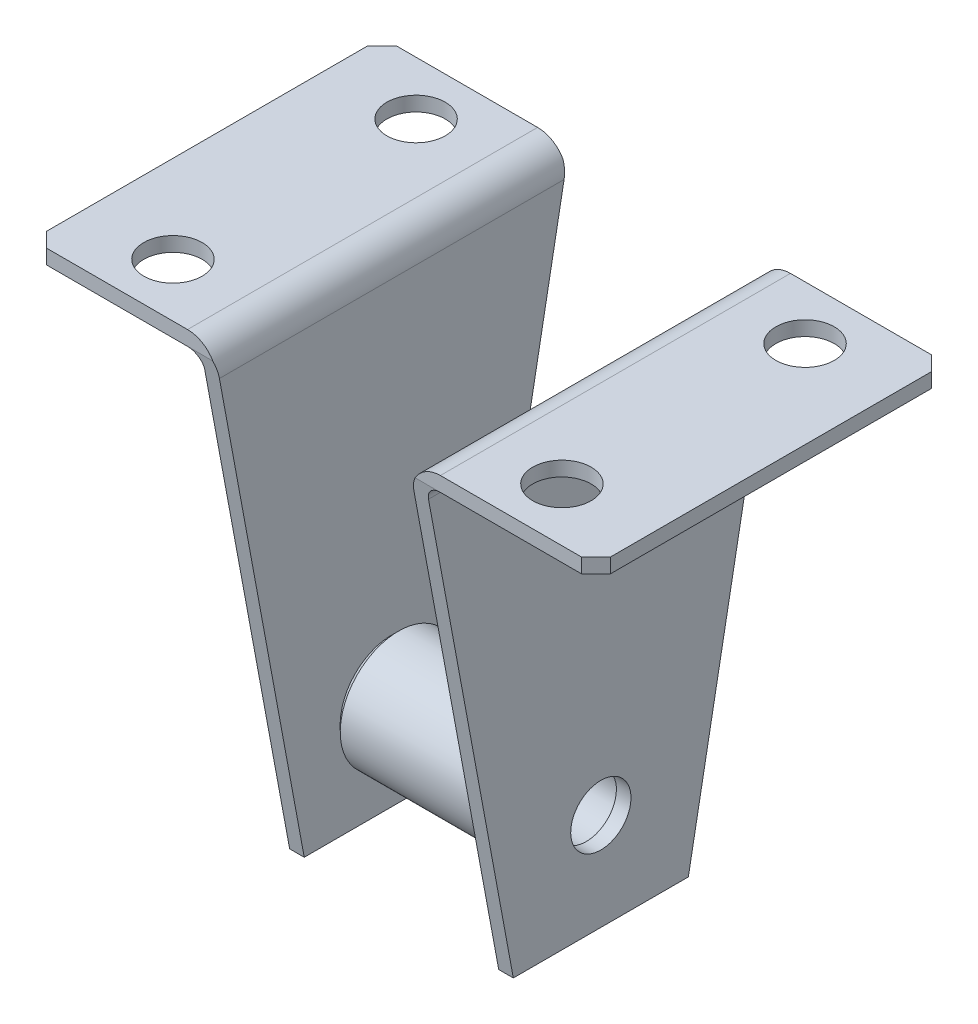
SolidWorks part; units mm, degrees
ref_plane "Front Plane" through (0, 0, 0) normal (0, 0, 1) x (1, 0, 0)
ref_plane "Top Plane" through (0, 0, 0) normal (0, 1, 0) x (1, 0, 0)
ref_plane "Right Plane" through (0, 0, 0) normal (1, 0, 0) x (0, 0, -1)
sketch "Sketch1" plane through (0, 0, 0) normal (0, 0, 1) x (1, 0, 0)
  line L0 (-13, 0) -> (-29, 0)
  line L1 (-10, -3) -> (-10, -50)
  line L2 (-11.5, -3) -> (-11.5, -50)
  line L3 (-13, -1.5) -> (-29, -1.5)
  line L4 (-29, 0) -> (-29, -1.5)
  line L5 (-11.5, -50) -> (-10, -50)
  line L6 (0, 0) -> (0, -50) construction
  line L7 (11.5, -50) -> (10, -50)
  line L8 (29, 0) -> (29, -1.5)
  line L9 (13, -1.5) -> (29, -1.5)
  line L10 (11.5, -3) -> (11.5, -50)
  line L11 (10, -3) -> (10, -50)
  line L12 (13, 0) -> (29, 0)
  arc A0 (-13, 0) -> (-10, -3) centre (-13, -3) cw
  arc A1 (-13, -1.5) -> (-11.5, -3) centre (-13, -3) cw
  arc A2 (13, -1.5) -> (11.5, -3) centre (13, -3) ccw
  arc A3 (13, 0) -> (10, -3) centre (13, -3) ccw
  dimension "FIX_5" = 3
  dimension "FIX_1" = 50
  dimension "FIX_3" = 58
  dimension "FIX_4" = 20
  dimension "FIX_2" = 1.5
extrude "Boss-Extrude1" add sketch "Sketch1" along normal mid plane 36
sketch "Sketch2" plane through (0, 0, 0) normal (1, 0, 0) x (0, 0, -1)
  line L0 (-18, -50) -> (-9, -50)
  line L1 (-9, -50) -> (-18, -1.5)
  line L2 (-18, -1.5) -> (-18, -50)
  line L3 (9, -50) -> (18, -50)
  line L4 (18, -50) -> (18, -1.5)
  line L5 (18, -1.5) -> (9, -50)
  line L6 (0, 0) -> (0, -50) construction
  dimension "FIX_7" = 9
  dimension "FIX_8" = 36
extrude "Cut-Extrude1" cut sketch "Sketch2" against normal through all and the other way through all
sketch "Sketch3" plane through (11.5, 0, 0) normal (1, 0, 0) x (0, 0, -1)
  circle A0 centre (0, -40) radius 3.1
  dimension "FIX_9" = 6.2
  dimension "FIX_10" = 40
extrude "Cut-Extrude2" cut sketch "Sketch3" against normal through all
sketch "Sketch4" plane through (0, 0, 0) normal (0, 0, 1) x (1, 0, 0)
  line L0 (-10, -40) -> (10, -40) construction
  line L1 (-10, -36.75) -> (10, -36.75)
  line L2 (10, -36.75) -> (10, -34.7)
  line L3 (10, -34.7) -> (9.3, -34)
  line L4 (9.3, -34) -> (-9.3, -34)
  line L5 (-9.3, -34) -> (-10, -34.7)
  line L6 (-10, -34.7) -> (-10, -36.75)
  line L7 (10, -3) -> (10, -50) construction
  line L8 (-10, -3) -> (-10, -50) construction
  dimension "FIX_11" = 40
  dimension "FIX_14" = 6.5
  dimension "FIX_15" = 12
  dimension "FIX_12" = 0.7
  dimension "FIX_13" = 45
revolve "Revolve1" add sketch "Sketch4" angle 360 about L0
sketch "Sketch5" plane through (0, 0, 0) normal (0, 1, 0) x (1, 0, 0)
  line L0 (-20, 12.5) -> (20, 12.5) construction
  line L1 (20, 12.5) -> (20, -12.5) construction
  line L2 (20, -12.5) -> (-20, -12.5) construction
  line L3 (-20, -12.5) -> (-20, 12.5) construction
  circle A0 centre (-20, 12.5) radius 3
  circle A1 centre (-20, -12.5) radius 3
  circle A2 centre (20, 12.5) radius 3
  circle A3 centre (20, -12.5) radius 3
  point P8 (0, 12.5)
  point P9 (-20, 0)
  dimension "FIX_19" = 6
  dimension "FIX_17" = 40
  dimension "FIX_18" = 25
extrude "Cut-Extrude3" cut sketch "Sketch5" against normal through all
chamfer "Chamfer1" distance 1.5 4 edges at (29, -0.75, -18) (29, -0.75, 18) (-29, -0.75, -18) (-29, -0.75, 18)
